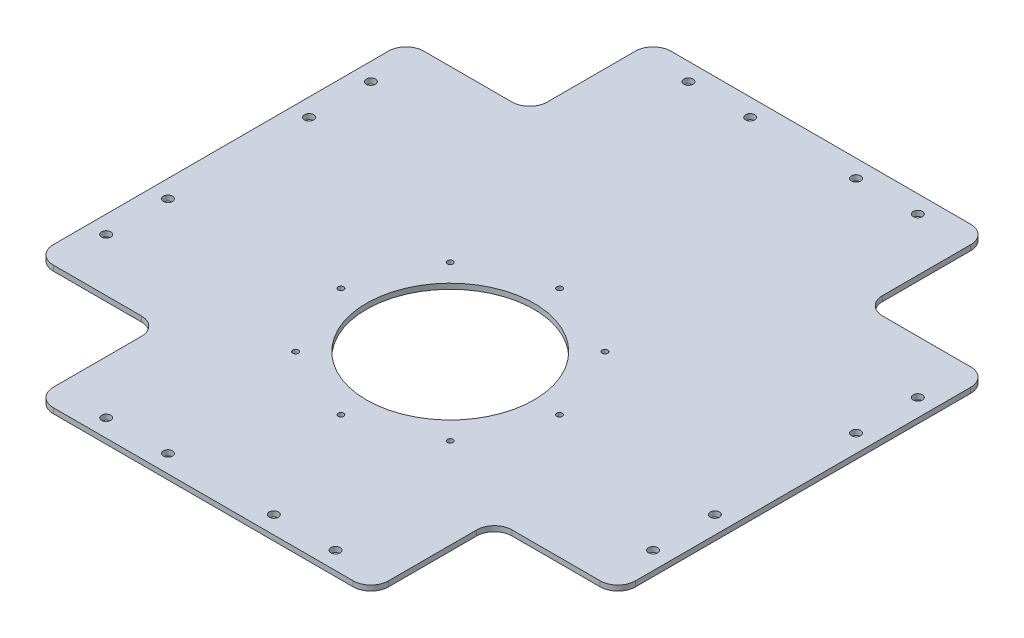
SolidWorks part; units mm, degrees
ref_plane "Front Plane" through (0, 0, 0) normal (0, 0, 1) x (1, 0, 0)
ref_plane "Top Plane" through (0, 0, 0) normal (0, 1, 0) x (1, 0, 0)
ref_plane "Right Plane" through (0, 0, 0) normal (1, 0, 0) x (0, 0, -1)
sketch "Sketch1" plane through (0, 0, 0) normal (0, 1, 0) x (1, 0, 0)
  line L0 (0, 140) -> (330, 140) construction
  line L1 (0, 0) -> (330, 0) construction
  line L2 (0, 0) -> (0, 350) construction
  line L3 (0, 350) -> (330, 350) construction
  line L4 (330, 0) -> (330, 350) construction
  line L5 (0, 0) -> (330, 0)
  line L6 (0, 0) -> (0, 280)
  line L7 (0, 280) -> (330, 280)
  line L8 (330, 0) -> (330, 280)
  line L9 (70, 280) -> (260, 280)
  line L10 (70, 280) -> (70, 350)
  line L11 (70, 350) -> (260, 350)
  line L12 (260, 280) -> (260, 350)
  line L14 (0, 0) -> (70, 0)
  line L15 (0, 0) -> (0, 70)
  line L16 (0, 70) -> (70, 70)
  line L17 (70, 0) -> (70, 70)
  line L18 (330, 0) -> (260, 0)
  line L19 (330, 0) -> (330, 70)
  line L20 (330, 70) -> (260, 70)
  line L21 (260, 0) -> (260, 70)
  circle A0 centre (165, 140) radius 56
  point P11 (165, 350)
  point P12 (165, 350)
  dimension "D5" = 112
  dimension "D1" = 330
  dimension "D2" = 350
  dimension "D3" = 70
  dimension "D4" = 70
  dimension "D6" = 70
extrude "Boss-Extrude1" add sketch "Sketch1" along normal blind 3 contours L5 L8 L7 L6 A0 | L7 L12 L11 L10
fillet "Fillet1" radius 10 12 edges at (330, 1.5, -280) (260, 1.5, -350) (260, 1.5, -280) (70, 1.5, -280) (70, 1.5, -350) (0, 1.5, -280) (260, 1.5, 0) (330, 1.5, -70) (260, 1.5, -70) (70, 1.5, 0) (70, 1.5, -70) (0, 1.5, -70)
sketch "Sketch2" plane through (0, 3, 0) normal (0, 1, 0) x (1, 0, 0)
  line L0 (80, 350) -> (250, 350) construction
  line L1 (0, 0) -> (330, 0) construction
  line L2 (0, 0) -> (0, 350) construction
  line L3 (0, 350) -> (330, 350) construction
  line L4 (330, 0) -> (330, 350) construction
  line L5 (330, 80) -> (330, 270) construction
  line L6 (10, 10) -> (10, 340) construction
  line L7 (10, 340) -> (320, 340) construction
  line L8 (320, 10) -> (320, 340) construction
  line L9 (10, 10) -> (320, 10) construction
  line L10 (70, 290) -> (70, 340) construction
  line L11 (260, 290) -> (260, 340) construction
  line L12 (270, 280) -> (320, 280) construction
  line L13 (260, 10) -> (260, 60) construction
  line L14 (70, 10) -> (70, 60) construction
  line L15 (320, 70) -> (270, 70) construction
  line L16 (10, 70) -> (60, 70) construction
  line L17 (10, 280) -> (60, 280) construction
  circle A0 centre (100, 340) radius 2.6
  circle A1 centre (135, 340) radius 2.6
  circle A2 centre (195, 340) radius 2.6
  circle A3 centre (230, 340) radius 2.6
  circle A4 centre (10, 250) radius 2.6
  circle A5 centre (10, 215) radius 2.6
  circle A6 centre (10, 100) radius 2.6
  circle A7 centre (10, 135) radius 2.6
  circle A8 centre (100, 10) radius 2.6
  circle A9 centre (135, 10) radius 2.6
  circle A10 centre (195, 10) radius 2.6
  circle A11 centre (230, 10) radius 2.6
  circle A12 centre (320, 100) radius 2.6
  circle A13 centre (320, 135) radius 2.6
  circle A14 centre (320, 250) radius 2.6
  circle A15 centre (320, 215) radius 2.6
  circle A16 centre (165, 140) radius 62 construction
  circle A17 centre (165, 140) radius 56 construction
  circle A18 centre (165, 202) radius 1.6
  circle A19 centre (208.8406, 183.8406) radius 1.6
  circle A20 centre (227, 140) radius 1.6
  circle A21 centre (208.8406, 96.1594) radius 1.6
  circle A22 centre (165, 78) radius 1.6
  circle A23 centre (121.1594, 96.1594) radius 1.6
  circle A24 centre (103, 140) radius 1.6
  circle A25 centre (121.1594, 183.8406) radius 1.6
  point P84 (165, 140)
  dimension "D2" = 5.2
  dimension "D4" = 35
  dimension "D5" = 35
  dimension "D7" = 30
  dimension "D8" = 35
  dimension "D10" = 35
  dimension "D12" = 35
  dimension "D14" = 35
  dimension "D16" = 35
  dimension "D17" = 30
  dimension "D18" = 35
  dimension "D19" = 6
  dimension "D20" = 3.2
  dimension "D3" = 30
  dimension "D6" = 30
  dimension "D9" = 30
  dimension "D11" = 30
  dimension "D13" = 30
  dimension "D15" = 30
  dimension "D1" = 10
  dimension "D21" = 8
extrude "Cut-Extrude1" cut sketch "Sketch2" against normal through all
sketch "Sketch3" plane through (0, 3, 0) normal (0, 1, 0) x (1, 0, 0)
  circle A0 centre (165, 140) radius 56
  circle A1 centre (165, 140) radius 47.5
  circle A2 centre (165, 140) radius 56 construction
  dimension "D1" = 95
extrude "Boss-Extrude2" add sketch "Sketch3" against normal up to surface (3 mm away) up to face at (320, 0, -132.4)
